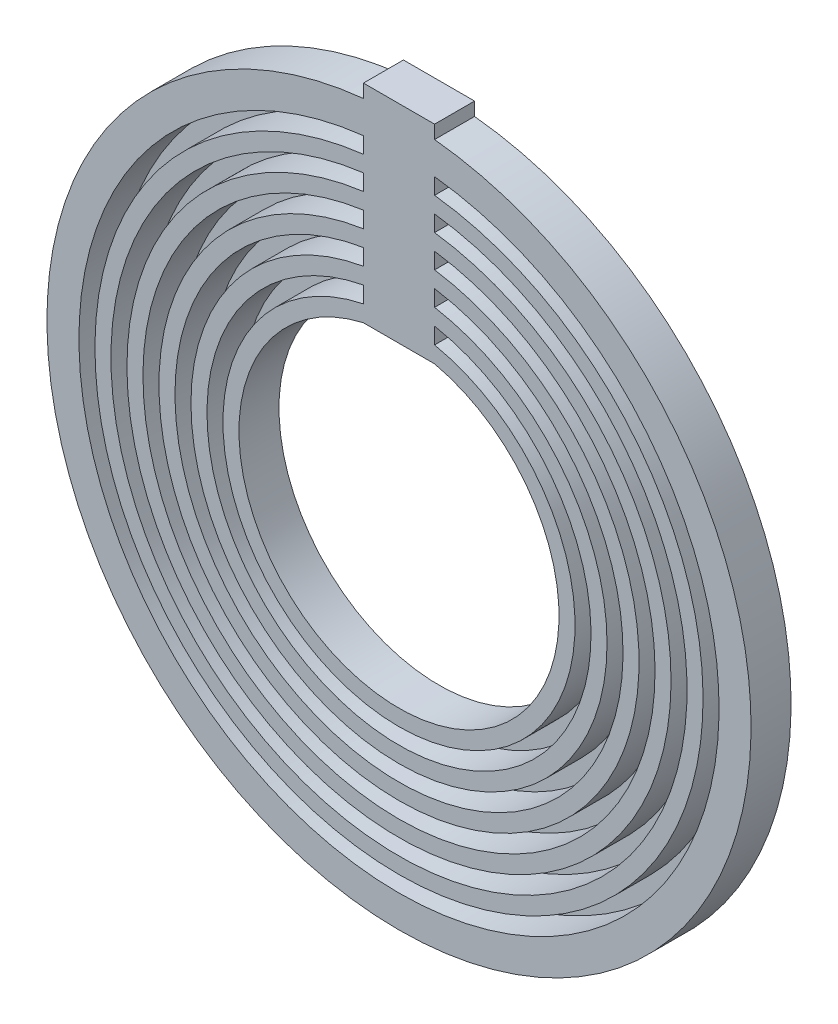
SolidWorks part; units mm, degrees
ref_plane "Alzado" through (0, 0, 0) normal (0, 0, 1) x (1, 0, 0)
ref_plane "Planta" through (0, 0, 0) normal (0, 1, 0) x (1, 0, 0)
ref_plane "Vista lateral" through (0, 0, 0) normal (1, 0, 0) x (0, 0, -1)
sketch "Croquis1" plane through (0, 0, 0) normal (0, 0, 1) x (1, 0, 0)
  circle A0 centre (0, 0) radius 22
  circle A1 centre (0, 0) radius 10
  dimension "D1" = 44
  dimension "D2" = 20
extrude "Saliente-Extruir1" add sketch "Croquis1" along normal blind 2.5
sketch "Croquis2" plane through (0, 0, 2.5) normal (0, 0, 1) x (1, 0, 0)
  circle A0 centre (0, 0) radius 10
  circle A1 centre (0, 0) radius 11
  circle A2 centre (0, 0) radius 12
  circle A3 centre (0, 0) radius 13
  circle A4 centre (0, 0) radius 14
  circle A5 centre (0, 0) radius 15
  circle A6 centre (0, 0) radius 16
  circle A7 centre (0, 0) radius 17
  circle A8 centre (0, 0) radius 18
  circle A9 centre (0, 0) radius 19
  circle A10 centre (0, 0) radius 20
  circle A11 centre (0, 0) radius 21
extrude "Cortar-Extruir1" cut sketch "Croquis2" against normal blind 2.25 contours A2 A1 | A4 A3 | A6 A5 | A8 A7 | A10 A9
sketch "Croquis3" plane through (0, 0, 2.5) normal (0, 0, 1) x (1, 0, 0)
  line L0 (0, 10) -> (0, 9.75)
  line L1 (0, 9.75) -> (-2.222, 9.75)
  line L2 (-2.222, 9.75) -> (2.222, 9.75)
  line L3 (2.222, 9.75) -> (2.222, 21.8875)
  line L4 (2.222, 21.8875) -> (2.222, 22.722)
  line L5 (2.222, 22.722) -> (-2.222, 22.722)
  line L6 (-2.222, 22.722) -> (-2.222, 9.75)
  circle A0 centre (0, 0) radius 10 construction
  circle A1 centre (0, 0) radius 22 construction
  dimension "D1" = 0.25
extrude "Saliente-Extruir2" add sketch "Croquis3" against normal blind 2.5
